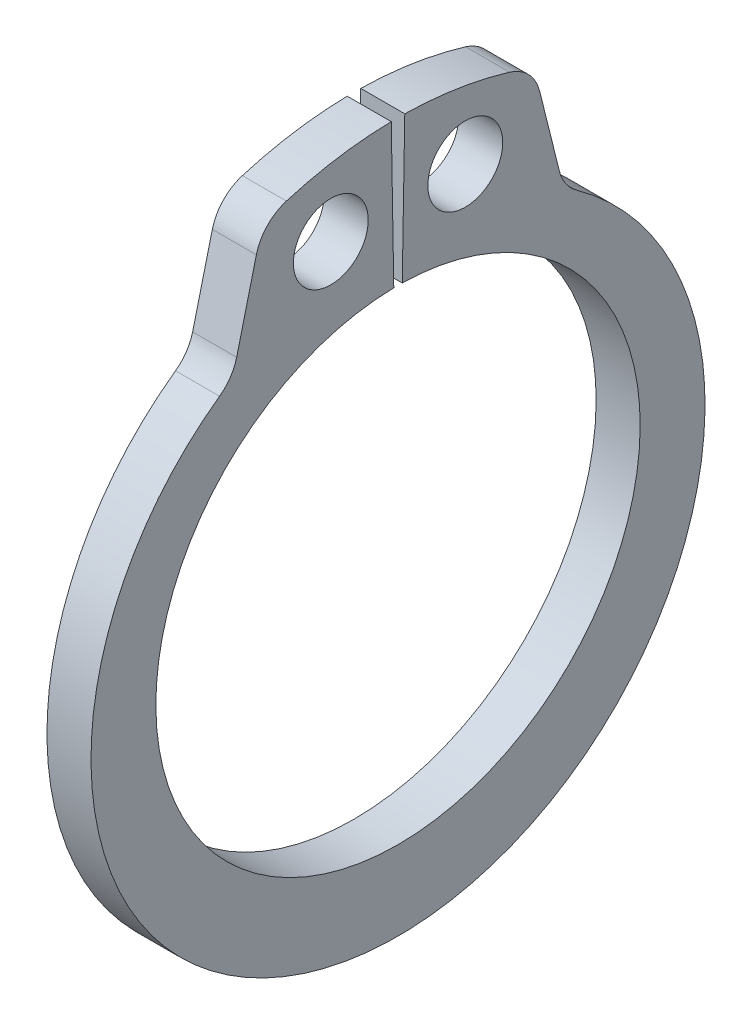
SolidWorks part; units mm, degrees
ref_plane "Front" through (0, 0, 0) normal (0, 0, 1) x (1, 0, 0)
ref_plane "Top" through (0, 0, 0) normal (0, 1, 0) x (1, 0, 0)
ref_plane "Right" through (0, 0, 0) normal (1, 0, 0) x (0, 0, -1)
sketch "Sketch1" plane through (0, 0, 0) normal (1, 0, 0) x (0, 0, -1)
  line L0 (0, 0) -> (0, 5.5) construction
  line L1 (-0.096, 5.4992) -> (-0.1536, 8.7987)
  line L2 (-0.1536, 8.7987) -> (-2.9583, 8.7497) construction
  line L3 (-2.9583, 8.7497) -> (-3.7567, 5.5477) construction
  line L4 (0.1536, 8.7987) -> (0.096, 5.4992)
  line L5 (0.1536, 8.7987) -> (2.9583, 8.7497) construction
  line L6 (2.9583, 8.7497) -> (3.7567, 5.5477) construction
  line L7 (-3.7567, 5.5477) -> (-3.0839, 4.5541) construction
  line L8 (3.7567, 5.5477) -> (3.0839, 4.5541) construction
  line L9 (0, -5.5) -> (0, -7.3) construction
  line L10 (-2.9583, 8.7497) -> (-0.096, 5.4992) construction
  line L12 (0, 5.5) -> (0, 8.8) construction
  line L13 (3.0851, 8.2415) -> (3.7567, 5.5477)
  line L14 (-3.0851, 8.2415) -> (-3.7567, 5.5477)
  circle A0 centre (0, 0) radius 5.5 construction
  arc A1 (-0.096, 5.4992) -> (0.096, 5.4992) centre (0, 0) ccw
  circle A2 centre (0, -0.3269) radius 6.9731 construction
  circle A4 centre (-1.5272, 7.1244) radius 0.85
  circle A5 centre (1.5272, 7.1244) radius 0.85
  arc A6 (-3.7567, 5.5477) -> (3.7567, 5.5477) centre (0, -0.3269) ccw
  arc A7 (0.1536, 8.7987) -> (3.0851, 8.2415) centre (0, 0) cw
  arc A8 (-0.1536, 8.7987) -> (-3.0851, 8.2415) centre (0, 0) ccw
  dimension "D1" = 75
  dimension "A" = 11
  dimension "Hole" = 1.7
  dimension "Smin" = 1.2
  dimension "Smax" = 1.8
  dimension "H" = 3.3
  dimension "Angle" = 1
extrude "Extrude1" add sketch "Sketch1" along normal mid plane 1
fillet "Fillet1" radius 1 4 edges at (0, 5.5477, 3.7567) (0, 8.2415, 3.0851) (0, 8.2415, -3.0851) (0, 5.5477, -3.7567)
sketch "Sketch2" plane through (0, 0, 0) normal (0, 0, 1) x (1, 0, 0)
  line L0 (-2.75, 0) -> (8.25, 0)
  line L1 (8.25, 0) -> (8.25, -6)
  line L2 (-2.75, 0) -> (-2.75, -5.75)
  line L3 (8.25, -6) -> (0.55, -6)
  line L4 (0.55, -6) -> (0.55, -5.75)
  line L5 (0.55, -5.75) -> (-0.55, -5.75)
  line L6 (-0.55, -5.75) -> (-0.55, -6)
  line L7 (-0.55, -6) -> (-2.75, -6) construction
  line L8 (-2.75, -6) -> (-2.75, 0) construction
  line L9 (0, -5.75) -> (0, 0) construction
  line L10 (8.25, 0) -> (14.0551, 0) construction
  line L11 (-2.75, -5.75) -> (-2.5, -6)
  line L12 (-2.5, -6) -> (-0.55, -6)
  dimension "D1" = 45
  dimension "Dg" = 11.5
  dimension "Ds" = 12
  dimension "D2" = 11
  dimension "W" = 1.1
  dimension "D3" = 2.75
revolve "Revolve1" [suppressed] add sketch "Sketch2" angle 360 about L10
equation "\"D2@Sketch2\" = \"W@Sketch2\"*10"
equation "\"D3@Sketch2\" = \"D2@Sketch2\"/4"
equation "\"Smin@Sketch1\" = \"Smax@Sketch1\"/1.5"
equation "\"D1@Fillet1\" = \"D1@Extrude1\""
